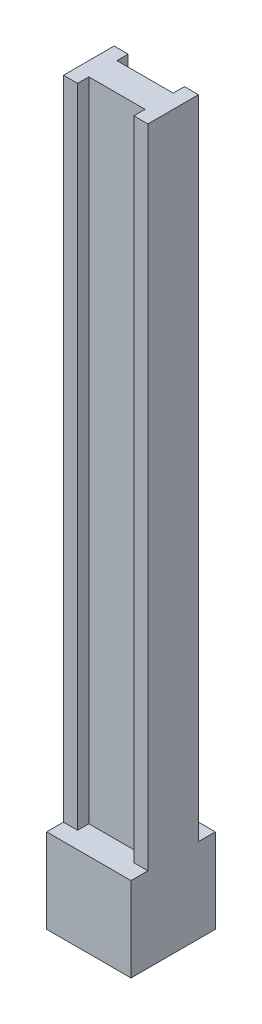
SolidWorks part; units mm, degrees
material "AISI 304"
ref_plane "Front Plane" through (0, 0, 0) normal (0, 0, 1) x (1, 0, 0)
ref_plane "Top Plane" through (0, 0, 0) normal (0, 1, 0) x (1, 0, 0)
ref_plane "Right Plane" through (0, 0, 0) normal (1, 0, 0) x (0, 0, -1)
sketch "Sketch2" plane through (0, 0, 0) normal (0, 1, 0) x (1, 0, 0)
  line L1 (-75, 75) -> (75, 75)
  line L2 (-75, 75) -> (-75, -75)
  line L3 (-75, -75) -> (75, -75)
  line L4 (75, 75) -> (75, -75)
  line L5 (-75, 75) -> (75, -75) construction
  line L6 (-75, -75) -> (75, 75) construction
  point P0 (0, 0)
  dimension "D1" = 150
  dimension "D2" = 150
extrude "Boss-Extrude1" add sketch "Sketch2" along normal blind 1300
sketch "Sketch3" plane through (0, 1300, 0) normal (0, 1, 0) x (-1, 0, 0)
  line L0 (-75, -75) -> (75, -75) construction
  line L1 (-50, -25) -> (50, -25)
  line L2 (-50, -25) -> (-50, -75)
  line L3 (-50, -75) -> (50, -75)
  line L4 (50, -25) -> (50, -75)
  line L5 (-50, -25) -> (50, -75) construction
  line L6 (-50, -75) -> (50, -25) construction
  line L7 (84.3437, 0) -> (-101.6201, 0) construction
  line L8 (-50, 75) -> (50, 25) construction
  line L9 (-50, 25) -> (50, 75) construction
  line L10 (50, 25) -> (50, 75)
  line L11 (-50, 75) -> (50, 75)
  line L12 (-50, 25) -> (-50, 75)
  line L13 (-50, 25) -> (50, 25)
  point P0 (0, -50)
  point P14 (0, 50)
  dimension "D1" = 100
  dimension "D2" = 50
extrude "Cut-Extrude3" cut sketch "Sketch3" against normal blind 1150
sketch "Sketch4" plane through (0, 1300, 0) normal (0, 1, 0) x (-1, 0, 0)
  line L0 (75, -75) -> (75, 75) construction
  line L1 (75, -45) -> (-75, -45)
  line L2 (75, -45) -> (75, -75)
  line L3 (75, -75) -> (-75, -75)
  line L4 (-75, -45) -> (-75, -75)
  line L5 (75, -45) -> (-75, -75) construction
  line L6 (75, -75) -> (-75, -45) construction
  line L7 (75, 0) -> (-75, 0) construction
  line L8 (-75, 75) -> (-75, -75) construction
  line L9 (75, 75) -> (-75, 45) construction
  line L10 (75, 45) -> (-75, 75) construction
  line L11 (-75, 45) -> (-75, 75)
  line L12 (75, 75) -> (-75, 75)
  line L13 (75, 45) -> (75, 75)
  line L14 (75, 45) -> (-75, 45)
  point P0 (0, -60)
  point P16 (0, 60)
  dimension "D1" = 30
extrude "Cut-Extrude4" cut sketch "Sketch4" against normal up to surface (1150 mm away) up to face at (0, 150, 50)
